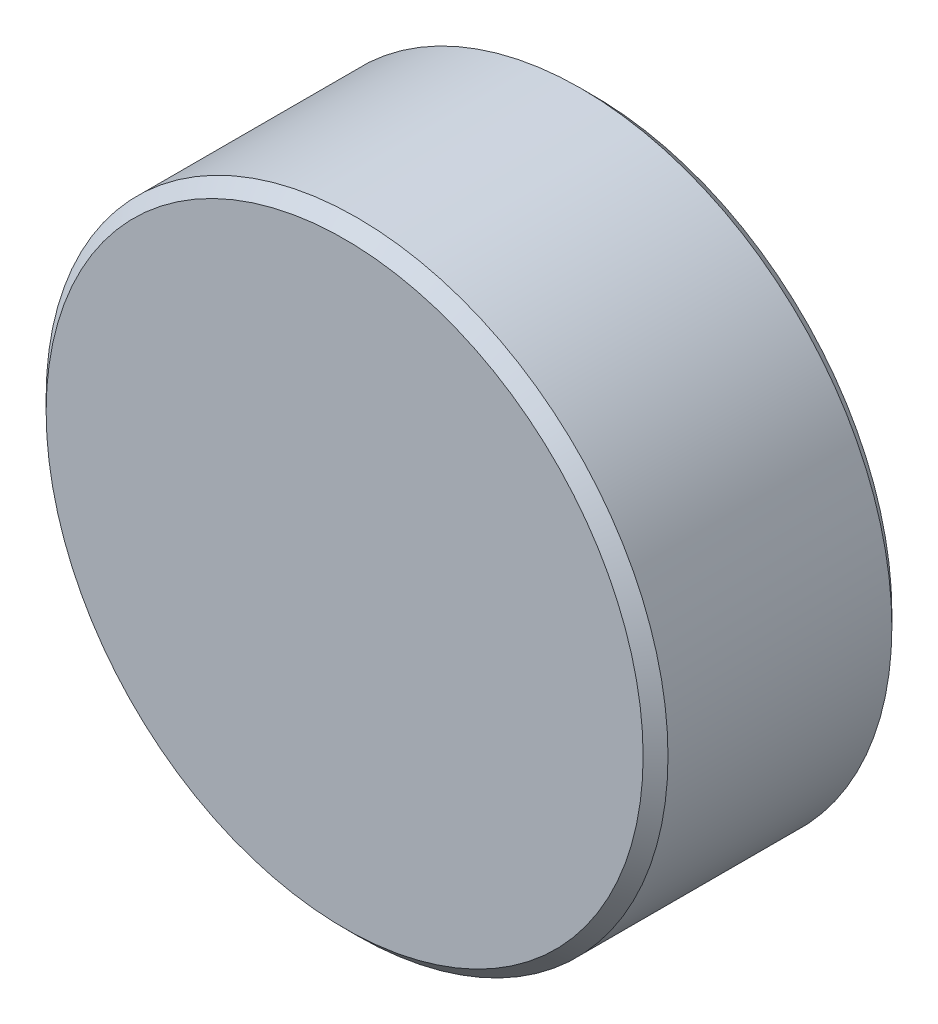
SolidWorks part; units mm, degrees
ref_plane "Front Plane" through (0, 0, 0) normal (0, 0, 1) x (1, 0, 0)
ref_plane "Top Plane" through (0, 0, 0) normal (0, 1, 0) x (1, 0, 0)
ref_plane "Right Plane" through (0, 0, 0) normal (1, 0, 0) x (0, 0, -1)
sketch "Sketch1" plane through (0, 0, 0) normal (0, 0, 1) x (1, 0, 0)
  circle A0 centre (0, 0) radius 3.175
  dimension "D1" = 6.35
extrude "Boss-Extrude1" add sketch "Sketch1" along normal blind 2.54
chamfer "Chamfer1" distance 0.127 angle 45 2 edges at (3.175, 0, 0) (3.175, 0, 2.54)
ref_plane "Plane1" through (0, 0, 2.413) normal (0, 0, 1) x (1, 0, 0)
